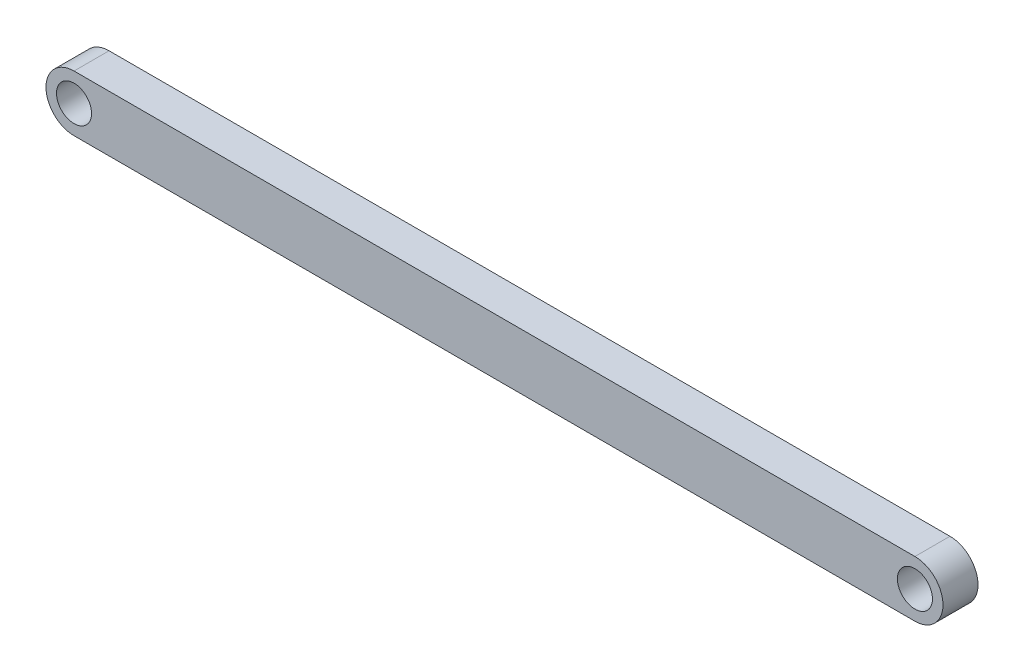
SolidWorks part; units mm, degrees
ref_plane "Front Plane" through (0, 0, 0) normal (0, 0, 1) x (1, 0, 0)
ref_plane "Top Plane" through (0, 0, 0) normal (0, 1, 0) x (1, 0, 0)
ref_plane "Right Plane" through (0, 0, 0) normal (1, 0, 0) x (0, 0, -1)
sketch "Sketch1" plane through (0, 0, 0) normal (0, 0, 1) x (1, 0, 0)
  line L0 (0, 0) -> (240, 0) construction
  line L5 (0, 8) -> (240, 8)
  line L6 (0, -8) -> (240, -8)
  arc A0 (0, 8) -> (0, -8) centre (0, 0) ccw
  arc A1 (240, -8) -> (240, 8) centre (240, 0) ccw
  circle A2 centre (240, 0) radius 5
  circle A3 centre (0, 0) radius 5
  point P2 (120, 0)
  dimension "D2" = 8
  dimension "D3" = 10
  dimension "D4" = 10
  dimension "D1" = 240
extrude "Boss-Extrude1" add sketch "Sketch1" along normal blind 10
